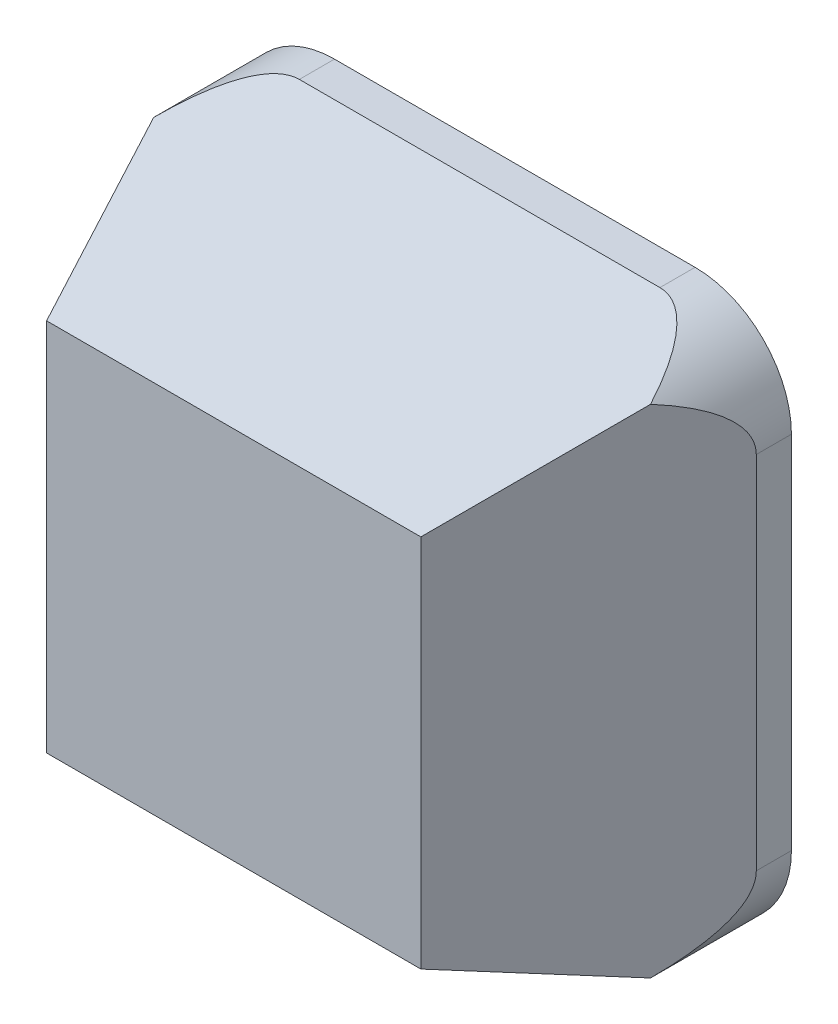
SolidWorks part; units mm, degrees
ref_plane "Front Plane" through (0, 0, 0) normal (0, 0, 1) x (1, 0, 0)
ref_plane "Top Plane" through (0, 0, 0) normal (0, 1, 0) x (1, 0, 0)
ref_plane "Right Plane" through (0, 0, 0) normal (1, 0, 0) x (0, 0, -1)
sketch "Sketch1" plane through (0, 0, 0) normal (0, 0, 1) x (1, 0, 0)
  line L0 (-12.5007, 8.1464) -> (-12.5007, -8.1464)
  line L1 (8.1464, 8.1464) -> (-8.1464, 8.1464) construction
  line L2 (8.1464, 8.1464) -> (8.1464, -8.1464) construction
  line L3 (8.1464, -8.1464) -> (-8.1464, -8.1464) construction
  line L4 (-8.1464, 8.1464) -> (-8.1464, -8.1464) construction
  line L5 (8.1464, 8.1464) -> (-8.1464, -8.1464) construction
  line L6 (8.1464, -8.1464) -> (-8.1464, 8.1464) construction
  line L7 (8.1464, 12.5007) -> (-8.1464, 12.5007)
  line L8 (12.5007, -8.1464) -> (12.5007, 8.1464)
  line L9 (-8.1464, -12.5007) -> (8.1464, -12.5007)
  line L10 (15960.2822, 15960.2822) -> (-15960.2822, -15960.2822) construction
  circle A0 centre (8.1464, 8.1464) radius 4.3543
  circle A1 centre (-8.1464, 8.1464) radius 4.3543
  circle A2 centre (-8.1464, -8.1464) radius 4.3543
  circle A3 centre (8.1464, -8.1464) radius 4.3543
  point P0 (0, 0)
  point P14 (-5.0674, -5.0674)
  point P21 (0, 0)
  point P22 (5.0674, 5.0674)
  point P23 (0, 0)
  point P24 (11.2253, 11.2253)
  point P25 (-37.5058, 0.0116)
  point P27 (-11.2253, -11.2253)
  dimension "D1" = 31.75
  dimension "D3" = 8.7086
  dimension "D4" = 12.5007
  dimension "D2" = 4
extrude "Boss-Extrude1" add sketch "Sketch1" along normal blind 12.7 contours A3 L8 A0 L7 A1 L0 A2 L9 | A1 | A2 | A0 | A3
sketch "Sketch2" plane through (0, 0, 0) normal (1, 0, 0) x (0, 0, -1)
  line L0 (-12.7, 12.5007) -> (-12.7, 8.1464) construction
  line L1 (-12.7, -8.1464) -> (-12.7, 8.1464) construction
  line L2 (-12.7, -8.1464) -> (-12.7, -12.5007) construction
  line L3 (-12.7, -12.5007) -> (0, -12.5007) construction
  line L4 (0, -12.5007) -> (0, -8.1464) construction
  line L5 (0, -8.1464) -> (0, 8.1464) construction
  line L6 (0, 8.1464) -> (0, 12.5007) construction
  line L7 (-12.7, 12.5007) -> (0, 12.5007) construction
  line L8 (-12.7, 12.5007) -> (-12.7, 8.1464) construction
  line L9 (-12.7, -8.1464) -> (-12.7, 8.1464) construction
  line L10 (-12.7, -8.1464) -> (-12.7, -12.5007) construction
  line L11 (-12.7, -12.5007) -> (0, -12.5007) construction
  line L12 (0, -12.5007) -> (0, -8.1464) construction
  line L13 (0, -8.1464) -> (0, 8.1464) construction
  line L14 (0, 8.1464) -> (0, 12.5007) construction
  line L15 (-12.7, 12.5007) -> (0, 12.5007) construction
  line L16 (-1.5875, 12.5007) -> (-1.5875, -12.5007) construction
  line L17 (-1.5875, 12.5007) -> (-12.7, 8.4561)
  line L18 (0, 0) -> (-50000, 0) construction
  line L19 (-1.5875, -12.5007) -> (-12.7, -8.4561)
  line L20 (-12.7, 8.4561) -> (-12.7, 12.5007)
  line L21 (-12.7, 12.5007) -> (-1.5875, 12.5007)
  line L22 (-12.7, -8.4561) -> (-12.7, -12.5007)
  line L23 (-12.7, -12.5007) -> (-1.5875, -12.5007)
  dimension "D1" = 1.5875
  dimension "D2" = 70
extrude "Cut-Extrude1" cut sketch "Sketch2" against normal mid plane 50.8 contours L21 L20 L17 | L19 L22 L23
sketch "Sketch3" plane through (0, 0, 0) normal (0, 1, 0) x (1, 0, 0)
  line L0 (-12.5007, -12.7) -> (-12.5007, 0) construction
  line L1 (12.5007, -12.7) -> (12.5007, 0) construction
  line L2 (-12.4896, -12.7) -> (12.4896, -12.7) construction
  line L3 (-8.1464, -1.5875) -> (8.1464, -1.5875) construction
  line L4 (-12.5007, -12.7) -> (-12.5007, 0) construction
  line L5 (12.5007, -12.7) -> (12.5007, 0) construction
  line L6 (-12.4896, -12.7) -> (12.4896, -12.7) construction
  line L7 (-8.1464, -1.5875) -> (8.1464, -1.5875) construction
  line L8 (0.2208, -1.5875) -> (50000.2208, -1.5875) construction
  line L9 (12.5007, -1.5875) -> (8.4561, -12.7)
  line L10 (12.5007, 0) -> (8.1464, 0) construction
  line L11 (8.4561, -12.7) -> (12.5007, -12.7)
  line L12 (12.5007, -12.7) -> (12.5007, -1.5875)
  line L13 (0, 0) -> (0, -50000) construction
  line L14 (-8.4561, -12.7) -> (-12.5007, -12.7)
  line L15 (-12.5007, -12.7) -> (-12.5007, -1.5875)
  line L16 (-12.5007, -1.5875) -> (-8.4561, -12.7)
  dimension "D1" = 1.5875
  dimension "D2" = 70
extrude "Cut-Extrude2" cut sketch "Sketch3" against normal mid plane 50.8
